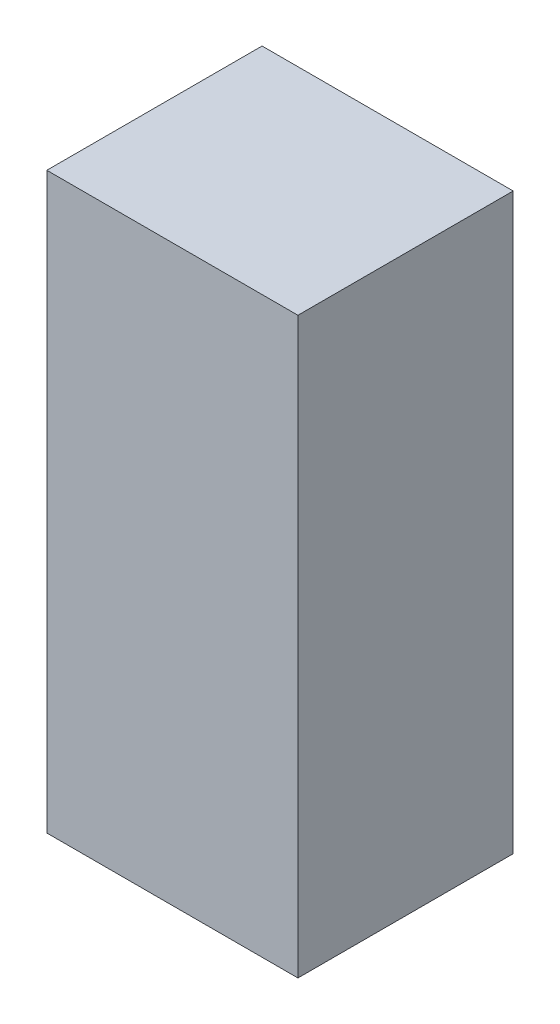
SolidWorks part; units mm, degrees
ref_plane "Front Plane" through (0, 0, 0) normal (0, 0, 1) x (1, 0, 0)
ref_plane "Top Plane" through (0, 0, 0) normal (0, 1, 0) x (1, 0, 0)
ref_plane "Right Plane" through (0, 0, 0) normal (1, 0, 0) x (0, 0, -1)
sketch "Sketch1" plane through (0, 0, 0) normal (0, 1, 0) x (1, 0, 0)
  line L1 (-1.75, 1.5) -> (1.75, 1.5)
  line L2 (-1.75, 1.5) -> (-1.75, -1.5)
  line L3 (-1.75, -1.5) -> (1.75, -1.5)
  line L4 (1.75, 1.5) -> (1.75, -1.5)
  line L5 (-1.75, 1.5) -> (1.75, -1.5) construction
  line L6 (-1.75, -1.5) -> (1.75, 1.5) construction
  point P0 (0, 0)
  dimension "D1" = 3
  dimension "D2" = 3.5
extrude "Boss-Extrude1" add sketch "Sketch1" along normal blind 8
